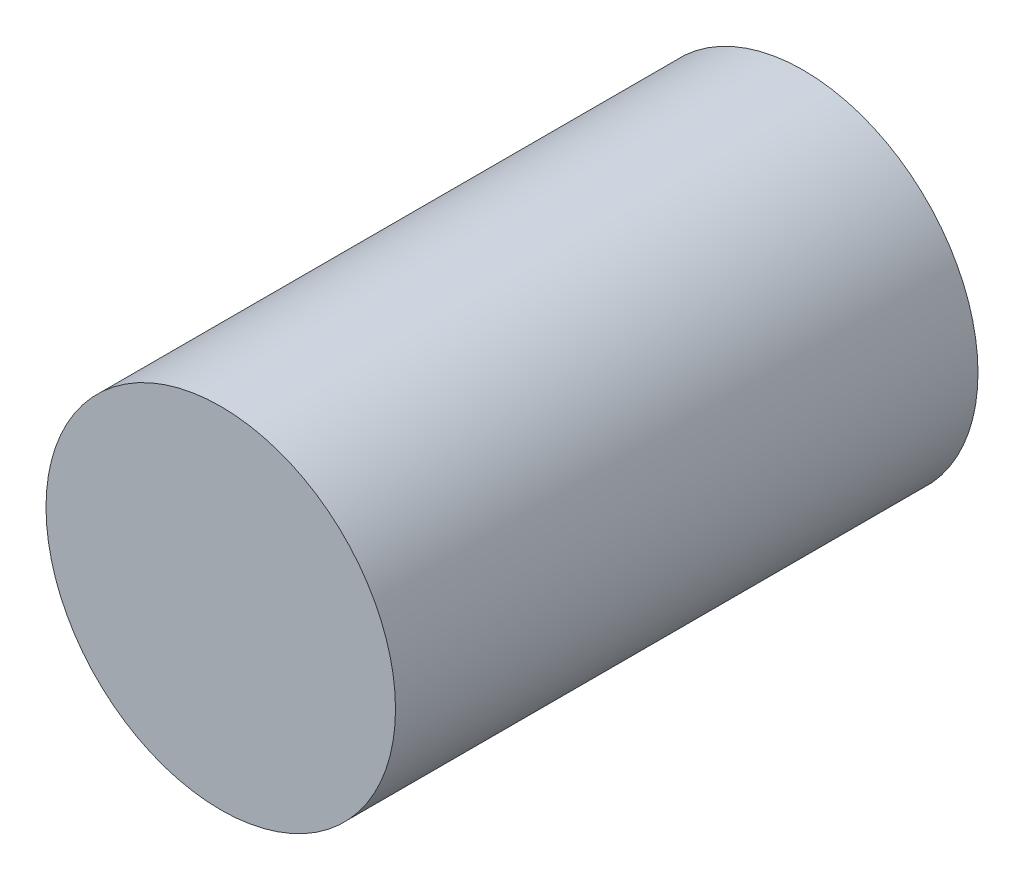
SolidWorks part; units mm, degrees
material "ｱｸﾘﾙ (中-上級の耐衝撃性)"
ref_plane "正面" through (0, 0, 0) normal (0, 0, 1) x (1, 0, 0)
ref_plane "平面" through (0, 0, 0) normal (0, 1, 0) x (1, 0, 0)
ref_plane "右側面" through (0, 0, 0) normal (1, 0, 0) x (0, 0, -1)
sketch "ｽｹｯﾁ1" plane through (0, 0, 0) normal (0, 0, 1) x (1, 0, 0)
  circle A0 centre (0, 0) radius 150
  dimension "D1" = 300
extrude "ﾎﾞｽ - 押し出し1" add sketch "ｽｹｯﾁ1" along normal blind 500
